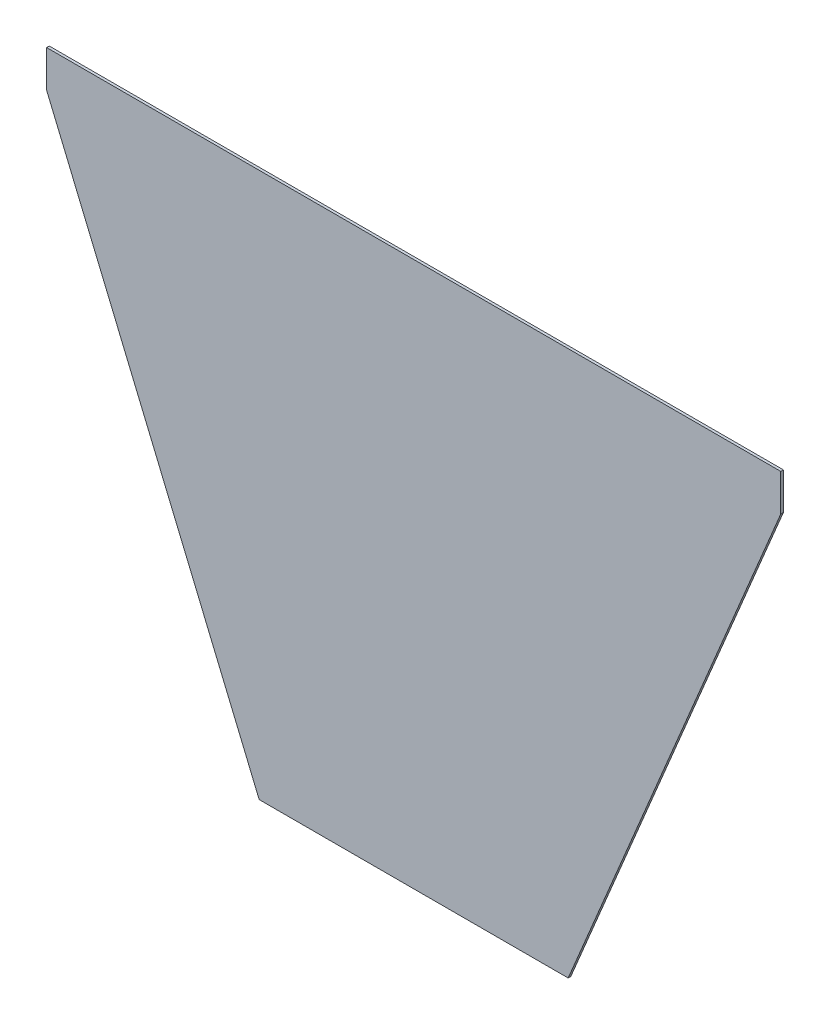
SolidWorks part; units mm, degrees
ref_plane "前视基准面" through (0, 0, 0) normal (0, 0, 1) x (1, 0, 0)
ref_plane "上视基准面" through (0, 0, 0) normal (0, 1, 0) x (1, 0, 0)
ref_plane "右视基准面" through (0, 0, 0) normal (1, 0, 0) x (0, 0, -1)
sketch "草图1" plane through (0, 0, 0) normal (0, 0, 1) x (1, 0, 0)
  line L0 (-695, 0) -> (695, 0)
  line L1 (-695, 0) -> (-695, -70)
  line L2 (-292.5, -1032) -> (292.5, -1032)
  line L3 (695, 0) -> (695, -70)
  line L4 (-695, -70) -> (-292.5, -1032)
  line L5 (695, -70) -> (292.5, -1032)
  line L6 (0, 244.6389) -> (0, -1227.8543) construction
  line L9 (-695, -1032) -> (695, -1032) construction
  dimension "D1" = 1390
  dimension "D3" = 70
  dimension "D4" = 70
  dimension "D5" = 585
  dimension "D2" = 1032
extrude "凸台-拉伸1" add sketch "草图1" along normal blind 5
